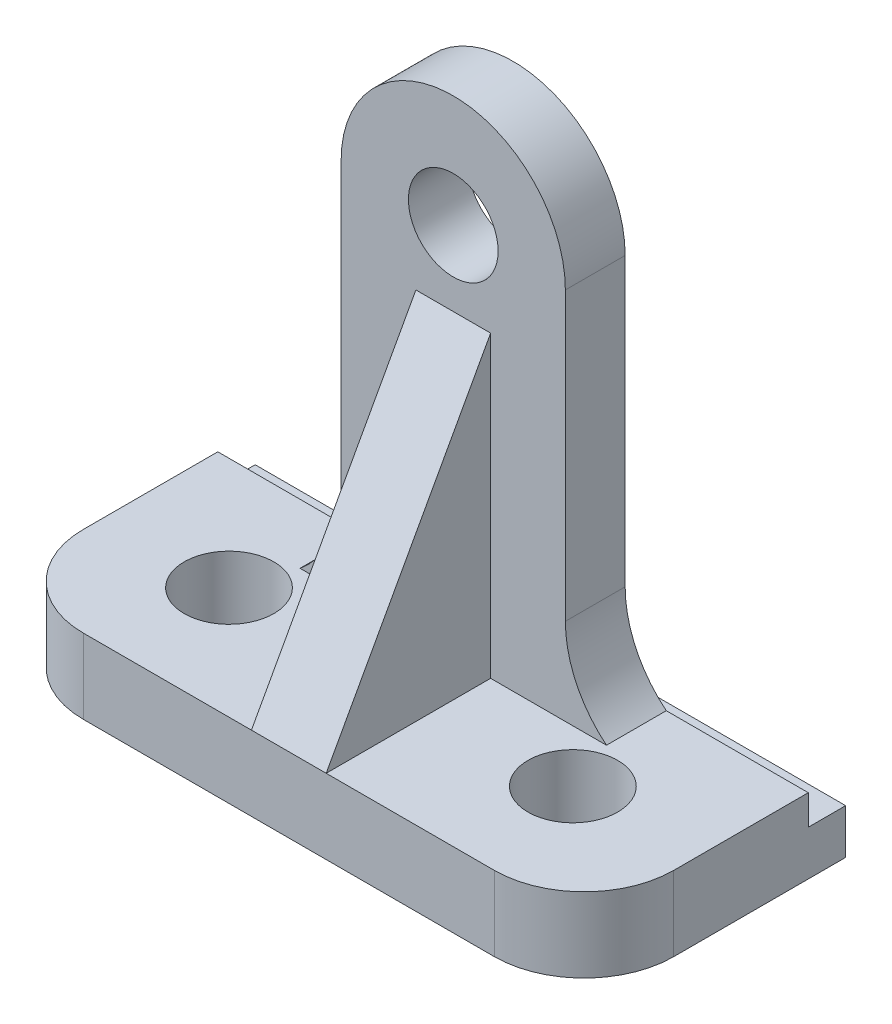
SolidWorks part; units mm, degrees
ref_plane "Front Plane" through (0, 0, 0) normal (0, 0, 1) x (1, 0, 0)
ref_plane "Top Plane" through (0, 0, 0) normal (0, 1, 0) x (1, 0, 0)
ref_plane "Right Plane" through (0, 0, 0) normal (1, 0, 0) x (0, 0, -1)
sketch "Sketch1" plane through (0, 0, 0) normal (0, 1, 0) x (1, 0, 0)
  line L0 (-105.9408, 0) -> (116.8065, 0) construction
  line L1 (-39.5, 0) -> (39.5, 0)
  line L2 (39.5, 0) -> (39.5, -23)
  line L3 (27.5, -35) -> (-27.5, -35)
  line L4 (-39.5, -23) -> (-39.5, 0)
  line L5 (0, -103.4184) -> (0, 79.3586) construction
  arc A0 (-27.5, -35) -> (-39.5, -23) centre (-27.5, -23) cw
  arc A1 (39.5, -23) -> (27.5, -35) centre (27.5, -23) cw
  point P15 (54.1829, -45.3861)
  dimension "D1" = 12
  dimension "D2" = 79
  dimension "D3" = 35
extrude "Boss-Extrude1" add sketch "Sketch1" along normal blind 10
sketch "Sketch2" plane through (39.5, 0, 0) normal (1, 0, 0) x (0, 0, -1)
  line L0 (0, 10) -> (0, 6)
  line L1 (0, 10) -> (0, 0) construction
  line L2 (0, 6) -> (-5, 6)
  line L3 (-5, 6) -> (-5, 10)
  line L4 (-23, 10) -> (0, 10) construction
  line L5 (-5, 10) -> (0, 10)
  dimension "D1" = 5
  dimension "D2" = 6
extrude "Cut-Extrude1" cut sketch "Sketch2" against normal up to surface (79 mm away) up to face at (-39.5, 5, 11.5)
sketch "Sketch5" plane through (0, 0, 0) normal (0, 0, 1) x (1, 0, 0)
  line L0 (-27.5, 10) -> (27.5, 10) construction
  line L1 (-15, 60) -> (-15, 21.6082)
  line L2 (15, 60) -> (15, 21.6082)
  line L3 (-20.5, 10) -> (20.5, 10)
  arc A0 (15, 60) -> (-15, 60) centre (0, 60) ccw
  arc A1 (-15, 21.6082) -> (-20.5, 10) centre (-30, 21.6082) cw
  arc A2 (15, 21.6082) -> (20.5, 10) centre (30, 21.6082) ccw
  dimension "D1" = 30
  dimension "D3" = 15
  dimension "D2" = 50
extrude "Boss-Extrude2" add sketch "Sketch5" along normal blind 13
sketch "Sketch6" plane through (15, 0, 0) normal (1, 0, 0) x (0, 0, -1)
  line L0 (0, 10) -> (-5, 10)
  line L1 (-5, 10) -> (-5, 75)
  line L2 (0, 75) -> (-13, 75) construction
  line L3 (-5, 75) -> (0, 75)
  line L4 (0, 75) -> (0, 10)
extrude "Cut-Extrude2" cut sketch "Sketch6" against normal through all both and the other way through all
sketch "Sketch7" plane through (0, 0, 13) normal (0, 0, 1) x (1, 0, 0)
  circle A0 centre (0, 60) radius 6
  dimension "D1" = 12
extrude "Cut-Extrude3" cut sketch "Sketch7" against normal blind 13
sketch "Sketch8" plane through (0, 0, 0) normal (1, 0, 0) x (0, 0, -1)
  line L0 (-35, 10) -> (-13, 50)
  line L1 (-13, 21.6082) -> (-13, 60) construction
  dimension "D1" = 40
rib "Rib1" sketch "Sketch8" sketch "Sketch8" thickness 10 extrusion direction parallel to sketch draft on no parameters "D1"=10
sketch "Sketch9" plane through (0, 10, 0) normal (0, 1, 0) x (1, 0, 0)
  line L2 (10.7286, -20) -> (35.8431, -20) construction
  line L3 (5, -35) -> (27.5, -35) construction
  line L4 (-39.5, -5) -> (39.5, -5) construction
  line L5 (0, 0) -> (0, -39.2619) construction
  circle A0 centre (23, -20) radius 6
  circle A1 centre (-23, -20) radius 6
  dimension "D1" = 12
  dimension "D2" = 23
extrude "Cut-Extrude4" cut sketch "Sketch9" against normal blind 13
